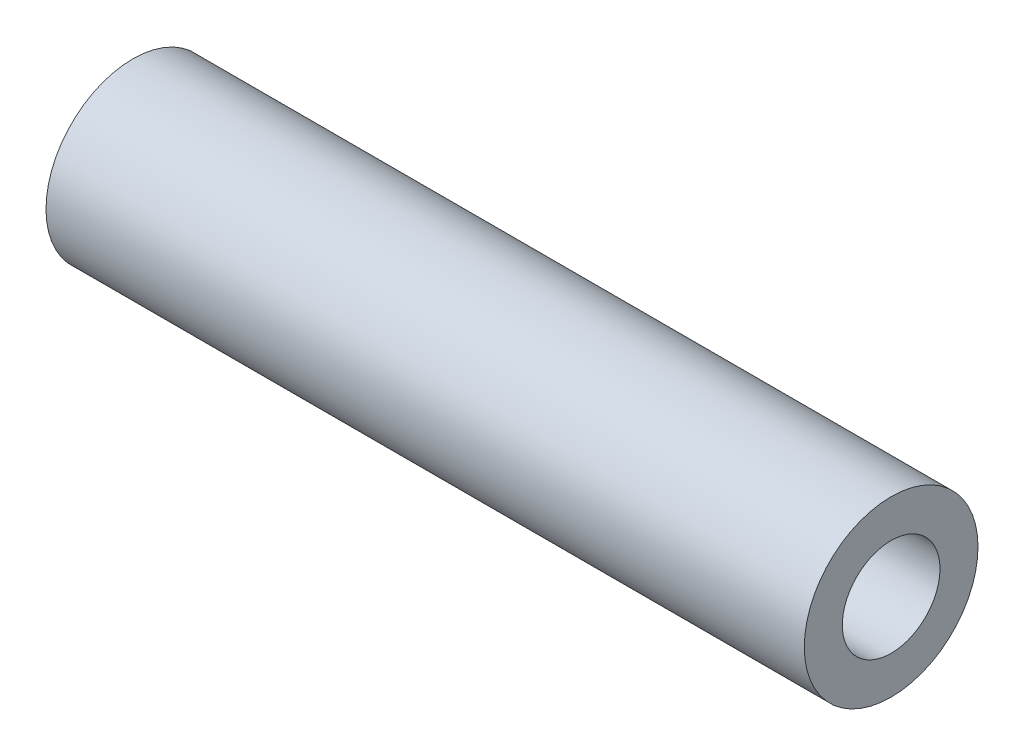
SolidWorks part; units mm, degrees
ref_plane "Front Plane" through (0, 0, 0) normal (0, 0, 1) x (1, 0, 0)
ref_plane "Top Plane" through (0, 0, 0) normal (0, 1, 0) x (1, 0, 0)
ref_plane "Right Plane" through (0, 0, 0) normal (1, 0, 0) x (0, 0, -1)
sketch "Sketch1" plane through (0, 0, 0) normal (1, 0, 0) x (0, 0, -1)
  circle A0 centre (0, 0) radius 4
  circle A1 centre (0, 0) radius 2.25
  dimension "D1" = 4.5
  dimension "D2" = 8
extrude "Boss-Extrude1" add sketch "Sketch1" along normal blind 34.925
